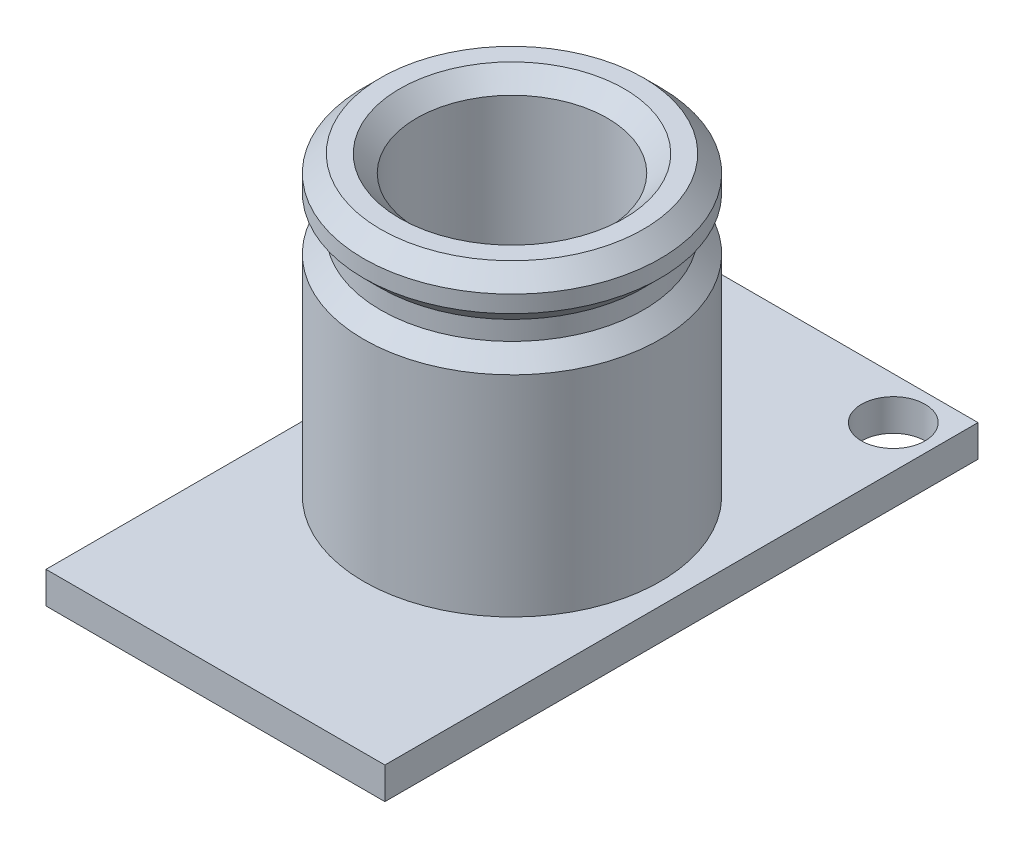
SolidWorks part; units mm, degrees
material "ABS"
ref_plane "Front Plane" through (0, 0, 0) normal (0, 0, 1) x (1, 0, 0)
ref_plane "Top Plane" through (0, 0, 0) normal (0, 1, 0) x (1, 0, 0)
ref_plane "Right Plane" through (0, 0, 0) normal (1, 0, 0) x (0, 0, -1)
sketch "Sketch1" plane through (0, 0, 0) normal (0, 1, 0) x (1, 0, 0)
  line L1 (-8, 14) -> (8, 14)
  line L2 (-8, 14) -> (-8, -14)
  line L3 (-8, -14) -> (8, -14)
  line L4 (8, 14) -> (8, -14)
  line L5 (0, -14) -> (0, 14) construction
  line L6 (-8, 0) -> (8, 0) construction
  point P0 (0, 0)
  dimension "D1" = 16
  dimension "D2" = 28
extrude "Boss-Extrude1" add sketch "Sketch1" along normal blind 1.5
sketch "Sketch5" plane through (0, 1.5, 0) normal (0, 1, 0) x (1, 0, 0)
  line L0 (-8, 14) -> (8, 14) construction
  line L1 (-8, 14) -> (-8, -14) construction
  circle A0 centre (-6, 12) radius 1.5
  dimension "D1" = 3
  dimension "D2" = 2
  dimension "D3" = 2
extrude "Cut-Extrude2" cut sketch "Sketch5" against normal through all
mirror "Mirror1" about plane through (0, 0, 0) normal (1, 0, 0) of "Cut-Extrude2"
sketch "Sketch2" plane through (0, 1.5, 0) normal (0, 1, 0) x (1, 0, 0)
  line L0 (0, -14) -> (0, 14) construction
  line L1 (-8, 0) -> (8, 0) construction
  circle A0 centre (0, 0) radius 7
  point P4 (0, 0)
  dimension "D1" = 14
extrude "Boss-Extrude2" add sketch "Sketch2" along normal blind 14 separate body
chamfer "Chamfer1" distance 0.8 angle 45 1 edges at (0, 15.5, 7)
sketch "Sketch3" plane through (0, 0, 0) normal (1, 0, 0) x (0, 0, -1)
  line L0 (7, 13.9) -> (6.2, 13.1)
  line L1 (7, 1.5) -> (7, 14.7) construction
  line L2 (6.2, 13.1) -> (6.2, 12.2)
  line L3 (6.2, 12.2) -> (7, 11.4)
  line L4 (7, 11.4) -> (7, 13.9)
  line L5 (-7, 14.7) -> (7, 14.7) construction
  line L6 (0, -1000) -> (0, 49000) construction
  dimension "D1" = 45
  dimension "D2" = 0.8
  dimension "D3" = 0.8
  dimension "D4" = 2.5
revolve "Cut-Revolve1" cut sketch "Sketch3" angle 360 about L6
sketch "Sketch4" plane through (0, 15.5, 0) normal (0, 1, 0) x (1, 0, 0)
  circle A0 centre (0, 0) radius 4.5
  point P3 (0, 0)
  dimension "D1" = 9
extrude "Cut-Extrude1" cut sketch "Sketch4" against normal blind 8
chamfer "Chamfer2" distance 0.8 angle 45 1 edges at (0, 15.5, 4.5)
